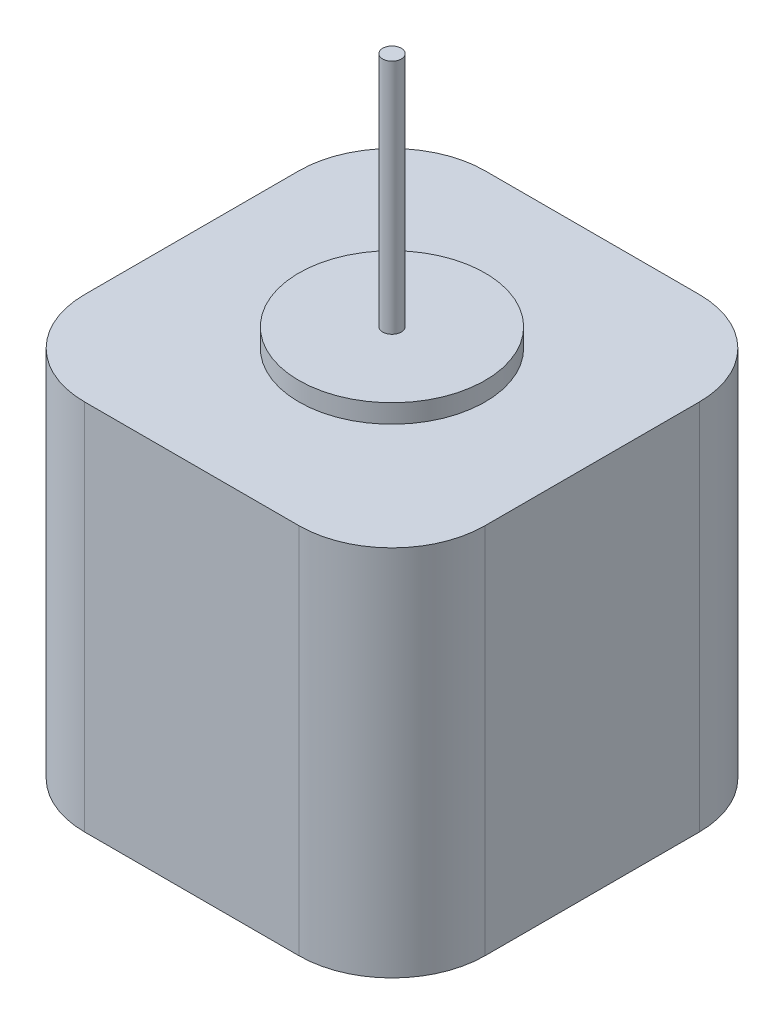
SolidWorks part; units mm, degrees
ref_plane "Front Plane" through (0, 0, 0) normal (0, 0, 1) x (1, 0, 0)
ref_plane "Top Plane" through (0, 0, 0) normal (0, 1, 0) x (1, 0, 0)
ref_plane "Right Plane" through (0, 0, 0) normal (1, 0, 0) x (0, 0, -1)
sketch "Sketch1" plane through (0, 0, 0) normal (0, 1, 0) x (1, 0, 0)
  line L1 (11.5, 21.5) -> (-11.5, 21.5)
  line L2 (21.5, 11.5) -> (21.5, -11.5)
  line L3 (11.5, -21.5) -> (-11.5, -21.5)
  line L4 (-21.5, 11.5) -> (-21.5, -11.5)
  line L5 (21.5, 21.5) -> (-21.5, -21.5) construction
  line L6 (21.5, -21.5) -> (-21.5, 21.5) construction
  arc A0 (11.5, 21.5) -> (21.5, 11.5) centre (11.5, 11.5) cw
  arc A1 (-11.5, -21.5) -> (-21.5, -11.5) centre (-11.5, -11.5) cw
  arc A2 (21.5, -11.5) -> (11.5, -21.5) centre (11.5, -11.5) cw
  arc A3 (-11.5, 21.5) -> (-21.5, 11.5) centre (-11.5, 11.5) ccw
  point P0 (0, 0)
  dimension "D3" = 10
  dimension "D1" = 43
  dimension "D2" = 43
extrude "Boss-Extrude1" add sketch "Sketch1" along normal blind 40
sketch "Sketch2" plane through (0, 40, 0) normal (0, 1, 0) x (1, 0, 0)
  circle A0 centre (0, 0) radius 10
  dimension "D1" = 20
extrude "Boss-Extrude2" add sketch "Sketch2" along normal blind 2
sketch "Sketch3" plane through (0, 42, 0) normal (0, 1, 0) x (1, 0, 0)
  circle A0 centre (0, 0) radius 1
  dimension "D1" = 2
extrude "Boss-Extrude3" add sketch "Sketch3" along normal blind 25.4
